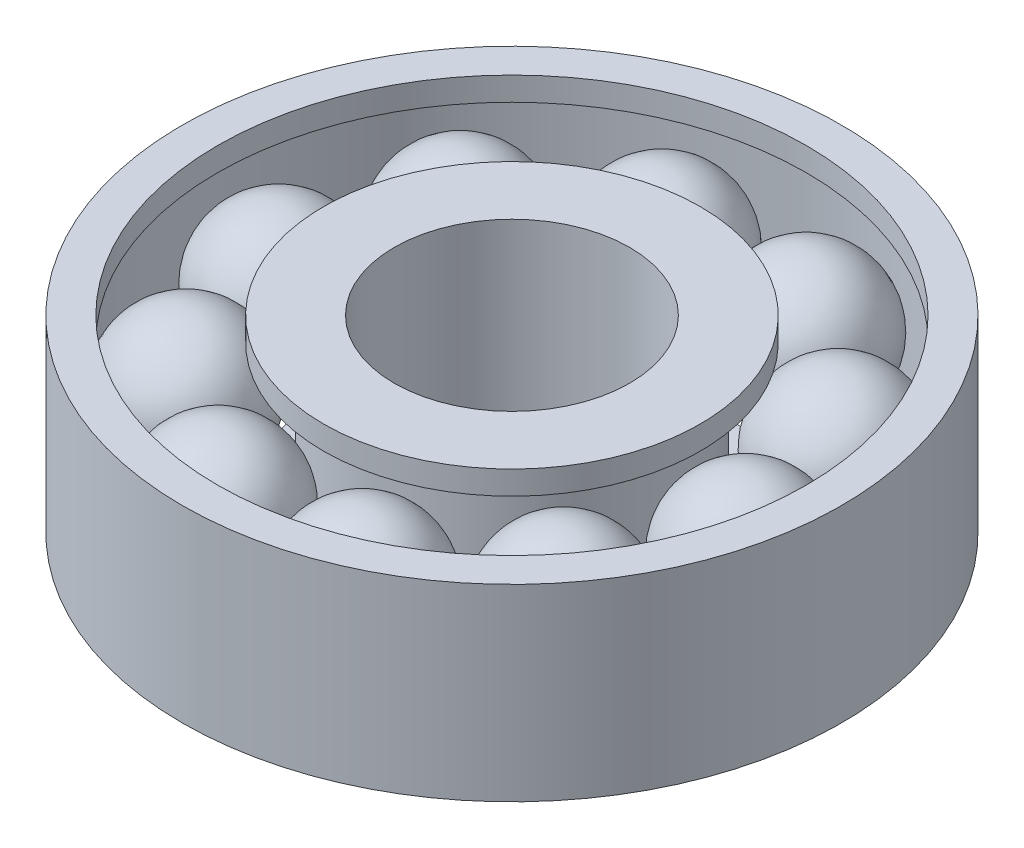
SolidWorks part; units mm, degrees
ref_plane "Front Plane" through (0, 0, 0) normal (0, 0, 1) x (1, 0, 0)
ref_plane "Top Plane" through (0, 0, 0) normal (0, 1, 0) x (1, 0, 0)
ref_plane "Right Plane" through (0, 0, 0) normal (1, 0, 0) x (0, 0, -1)
other "Graphic1"
other "Graphic (Closed) -1"
sketch "Sketch2" plane through (0, 0, 0) normal (0, 1, 0) x (1, 0, 0)
  circle A0 centre (0, 0) radius 12.5
  circle A1 centre (0, 0) radius 14
  dimension "D1" = 25
  dimension "D2" = 28
extrude "Boss-Extrude1" add sketch "Sketch2" along normal blind 8 from offset 3
sketch "Sketch5" plane through (0, 0, 0) normal (0, 1, 0) x (1, 0, 0)
  circle A0 centre (0, 0) radius 5
  circle A1 centre (0, 0) radius 8
  dimension "D1" = 10
  dimension "D2" = 16
extrude "Boss-Extrude2" add sketch "Sketch5" along normal blind 8 from offset 3 separate body
sketch "Sketch3" plane through (0, 0, 0) normal (0, 0, 1) x (1, 0, 0)
  line L0 (0, 11) -> (0, 3) construction
  line L1 (12.5, 11) -> (-12.5, 11) construction
  line L2 (-14, 3) -> (14, 3) construction
  line L4 (-13.25, 10) -> (-6.5, 10)
  line L5 (-13.25, 10) -> (-13.25, 4)
  line L6 (-13.25, 4) -> (-6.5, 4)
  line L8 (-6.5, 4) -> (-6.5, 10)
  line L11 (0, 9.5) -> (0, 4.5)
  line L12 (0, 9.5) -> (0, 4.5)
  point P6 (0, 7)
  dimension "D1" = 6
  dimension "D2" = 13.25
  dimension "D3" = 6.5
  dimension "D4" = 1
revolve "Cut-Revolve1" cut sketch "Sketch3" angle 360 about L0
sketch "Sketch6" plane through (0, 0, 0) normal (0, 0, 1) x (1, 0, 0)
  line L0 (7.2906, 10) -> (7.2906, 4) construction
  line L1 (-13.25, 10) -> (13.25, 10) construction
  line L2 (8, 4) -> (-8, 4) construction
  line L3 (9.9127, 7.2088) -> (13.2483, 7.2088) construction
  line L4 (9.5, 11) -> (10.3255, 11) construction
  line L5 (8, 11) -> (-8, 11) construction
  line L6 (12.5, 11) -> (-12.5, 11) construction
  line L7 (14, 11) -> (-14, 11) construction
  line L8 (9.9127, 11) -> (9.9127, 7.2088) construction
  line L9 (9.9127, 10.2088) -> (9.9127, 4.2088)
  arc A0 (9.9127, 4.2088) -> (9.9127, 10.2088) centre (9.9127, 7.2088) ccw
  arc A1 (7.2906, 8.6664) -> (7.2906, 5.7513) centre (9.9127, 7.2088) ccw
  dimension "D1" = 6
revolve "Revolve4" add sketch "Sketch6" angle 360 about L8
pattern_circular "CirPattern4" count 10 over 360 about axis through (0, 0, 0) along (0, 1, 0) of bodies 106
